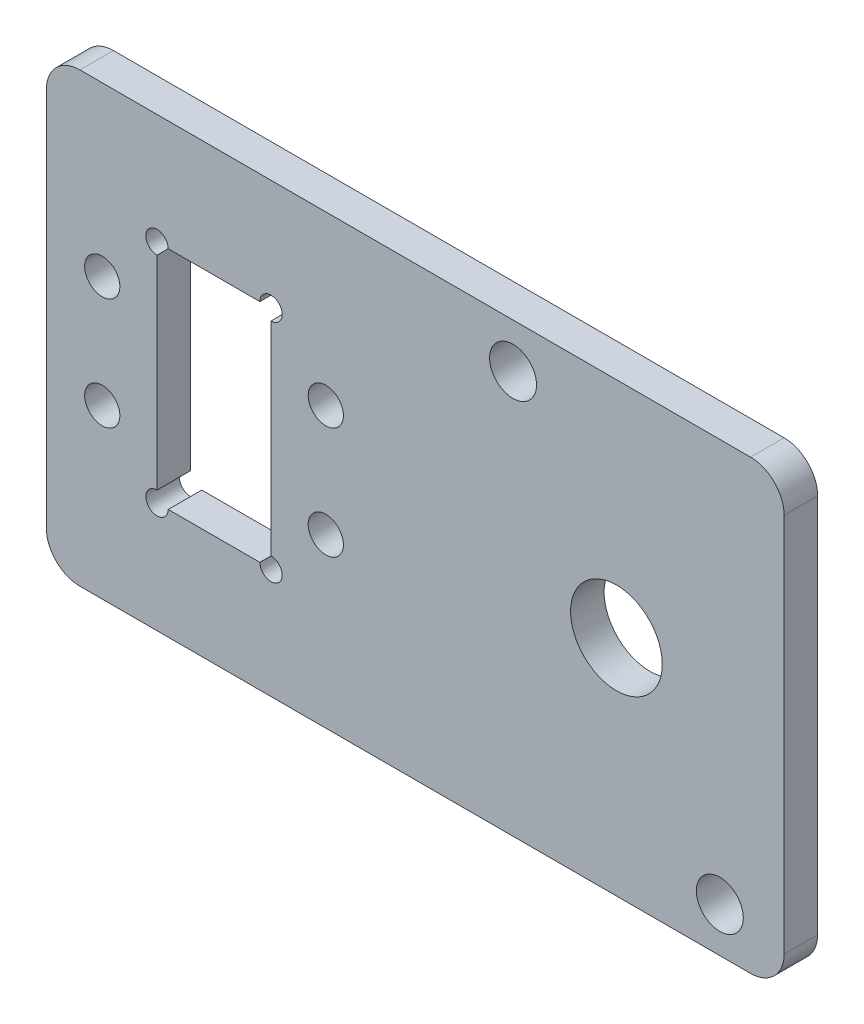
SolidWorks part; units mm, degrees
ref_plane "前视基准面" through (0, 0, 0) normal (0, 0, 1) x (1, 0, 0)
ref_plane "上视基准面" through (0, 0, 0) normal (0, 1, 0) x (1, 0, 0)
ref_plane "右视基准面" through (0, 0, 0) normal (1, 0, 0) x (0, 0, -1)
other "Configuration Table"
sketch "草图1" plane through (0, 0, 0) normal (0, 0, 1) x (1, 0, 0)
  line L0 (0, 0) -> (-66, 0)
  line L1 (-66, 0) -> (-66, -40)
  line L2 (-66, -40) -> (0, -40)
  line L3 (0, 0) -> (0, -40)
  dimension "D1" = 40
  dimension "D2" = 66
extrude "凸台-拉伸1" add sketch "草图1" along normal blind 3
sketch "草图2" plane through (0, 0, 3) normal (0, 0, 1) x (1, 0, 0)
  line L0 (-51, -9.9) -> (-51, -30.1) construction
  line L1 (-56.1, -9.9) -> (-45.9, -9.9)
  line L2 (-56.1, -9.9) -> (-56.1, -30.1)
  line L3 (-56.1, -30.1) -> (-45.9, -30.1)
  line L4 (-45.9, -9.9) -> (-45.9, -30.1)
  line L5 (-66, 0) -> (-66, -40) construction
  line L6 (-66, -20) -> (0, -20) construction
  line L7 (-15, -20) -> (-15, 0) construction
  line L8 (-15, -20) -> (-24.25, -3.9785) construction
  line L9 (0, -40) -> (0, 0) construction
  line L10 (0, 0) -> (-66, 0) construction
  line L11 (-15, -20) -> (-5.75, -36.0215) construction
  circle A1 centre (-61, -15) radius 1.575
  circle A2 centre (-61, -25) radius 1.575
  circle A3 centre (-41, -25) radius 1.575
  circle A4 centre (-41, -15) radius 1.575
  circle A5 centre (-15, -20) radius 4.1
  circle A9 centre (-24.25, -3.9785) radius 2.1
  circle A10 centre (-5.75, -36.0215) radius 2.1
  point P27 (-2.2721, -32.5016)
  point P34 (-15, -20)
  dimension "D4" = 5
  dimension "D6" = 3.15
  dimension "D7" = 8.2
  dimension "D8" = 18.5
  dimension "D10" = 4.2
  dimension "D13" = 4.2
  dimension "D1" = 20.2
  dimension "D2" = 10.2
  dimension "D3" = 15
  dimension "D5" = 10
  dimension "D9" = 60
  dimension "D11" = 15
  dimension "D12" = 18.5
extrude "切除-拉伸1" cut sketch "草图2" against normal through all
sketch "草图3" plane through (0, 0, 3) normal (0, 0, 1) x (1, 0, 0)
  circle A0 centre (-45.9, -9.9) radius 1
  circle A1 centre (-45.9, -30.1) radius 1
  circle A2 centre (-56.1, -30.1) radius 1
  circle A3 centre (-56.1, -9.9) radius 1
  dimension "D1" = 2
extrude "切除-拉伸2" cut sketch "草图3" against normal through all
fillet "圆角1" radius 3 4 edges at (-66, 0, 1.5) (-66, -40, 1.5) (0, -40, 1.5) (0, 0, 1.5)
